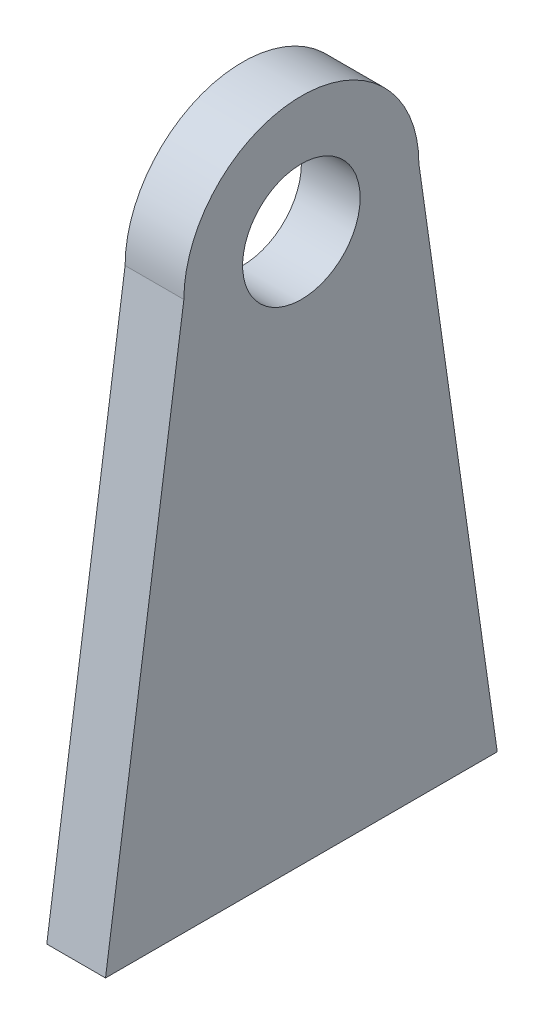
SolidWorks part; units mm, degrees
ref_plane "Front Plane" through (0, 0, 0) normal (0, 0, 1) x (1, 0, 0)
ref_plane "Top Plane" through (0, 0, 0) normal (0, 1, 0) x (1, 0, 0)
ref_plane "Right Plane" through (0, 0, 0) normal (1, 0, 0) x (0, 0, -1)
sketch "Sketch1" plane through (0, 0, 0) normal (1, 0, 0) x (0, 0, -1)
  line L0 (0, 0) -> (40, 0)
  line L1 (40, 0) -> (32, 56)
  line L2 (0, 0) -> (8, 56)
  arc A0 (32, 56) -> (8, 56) centre (20, 56) ccw
  circle A1 centre (20, 56) radius 6
  point P8 (20, 0)
  dimension "D4" = 24
  dimension "D5" = 12
  dimension "D1" = 40
  dimension "D2" = 56
  dimension "D3" = 56
extrude "Boss-Extrude1" add sketch "Sketch1" along normal blind 6
